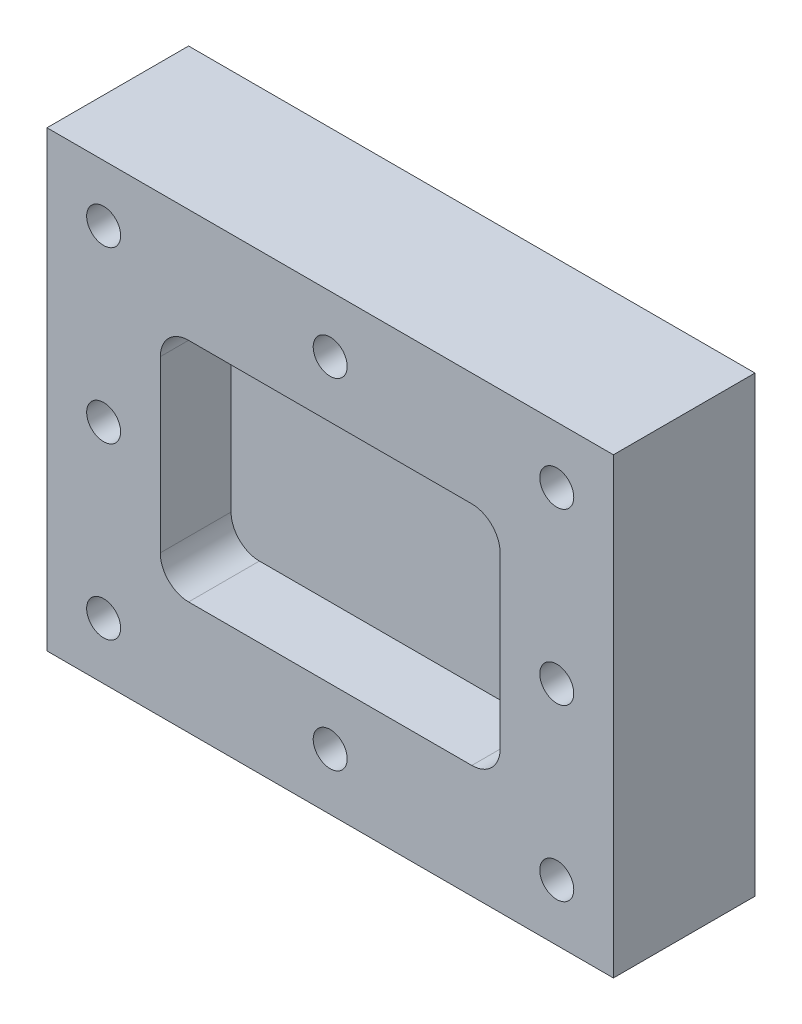
SolidWorks part; units mm, degrees
ref_plane "Plane1" through (0, 0, 0) normal (0, 0, 1) x (1, 0, 0)
ref_plane "Plane2" through (0, 0, 0) normal (0, 1, 0) x (1, 0, 0)
ref_plane "Plane3" through (0, 0, 0) normal (1, 0, 0) x (0, 0, -1)
sketch "Sketch1" plane through (0, 0, 0) normal (0, 0, 1) x (1, 0, 0)
  line L0 (-100, 80) -> (100, 80)
  line L1 (-100, 80) -> (-100, -80)
  line L2 (100, -80) -> (-100, -80)
  line L3 (100, -80) -> (100, 80)
extrude "Base-Extrude" add sketch "Sketch1" against normal blind 50
sketch "Sketch2" plane through (0, 0, 0) normal (0, 0, 1) x (1, 0, 0)
  line L0 (-50, 40) -> (50, 40)
  line L1 (-60, 30) -> (-60, -30)
  line L2 (50, -40) -> (-50, -40)
  line L3 (60, -30) -> (60, 30)
  arc A0 (-60, 30) -> (-50, 40) centre (-50, 30) cw
  arc A1 (-50, -40) -> (-60, -30) centre (-50, -30) cw
  arc A2 (60, -30) -> (50, -40) centre (50, -30) cw
  arc A3 (60, 30) -> (50, 40) centre (50, 30) ccw
  dimension "D1" = 10
extrude "Cut-Extrude1" cut sketch "Sketch2" against normal blind 25
sketch "Sketch3" plane through (0, 0, 0) normal (0, 0, 1) x (1, 0, 0)
  line L1 (-50, 40) -> (50, 40) construction
  circle A0 centre (-80, 60) radius 6
  circle A1 centre (-80, 0) radius 6
  circle A2 centre (-80, -60) radius 6
  circle A3 centre (80, -60) radius 6
  circle A4 centre (80, 0) radius 6
  circle A5 centre (80, 60) radius 6
  circle A6 centre (0, -60) radius 6
  circle A7 centre (0, 60) radius 6
  dimension "D1" = 12
  dimension "D2" = 12
  dimension "D3" = 20
  dimension "D4" = 12
  dimension "D5" = 12
  dimension "D6" = 12
  dimension "D7" = 12
  dimension "D8" = 12
  dimension "D9" = 12
extrude "Cut-Extrude2" cut sketch "Sketch3" against normal through all
